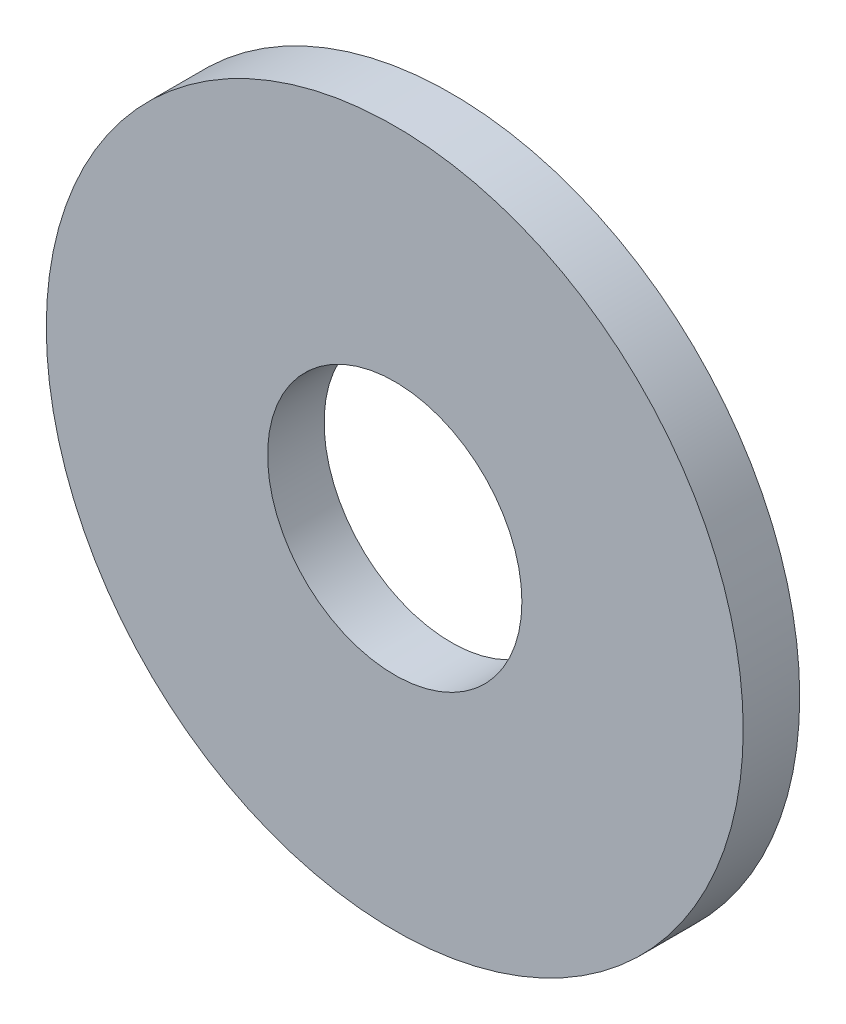
SolidWorks part; units mm, degrees
material "Nylon 101"
ref_plane "Front Plane" through (0, 0, 0) normal (0, 0, 1) x (1, 0, 0)
ref_plane "Top Plane" through (0, 0, 0) normal (0, 1, 0) x (1, 0, 0)
ref_plane "Right Plane" through (0, 0, 0) normal (1, 0, 0) x (0, 0, -1)
sketch "Sketch1" plane through (0, 0, 0) normal (0, 0, 1) x (1, 0, 0)
  circle A0 centre (0, 0) radius 7.4 construction
  circle A1 centre (0, 0) radius 2.7 construction
  point P5 (-2.7, 0)
  point P6 (2.7, 0)
  point P7 (7.4, 0)
  point P8 (-7.4, 0)
  point P9 (0, -2.7)
  dimension "OD" = 14.8
  dimension "ID" = 5.4
sketch "Sketch2" plane through (0, 0, 0) normal (1, 0, 0) x (0, 0, -1)
  line L0 (0.6, 0) -> (-0.6, 0) construction
  line L1 (0, 7.4) -> (0, -7.4) construction
  line L2 (0, 7.4) -> (0, -7.4) construction
  line L3 (0.6, 7.4) -> (-0.6, 7.4) construction
  line L4 (0.6, -7.4) -> (-0.6, -7.4) construction
  line L5 (-0.6, -7.4) -> (-0.6, 7.4) construction
  line L6 (0.6, -7.4) -> (0.6, 7.4) construction
  point P4 (0, 0)
  point P10 (0, 7.4)
  point P11 (-0.6, 7.4)
  point P14 (0, -7.4)
  point P15 (-0.6, -7.4)
  point P16 (0.6, -7.4)
  point P17 (0.6, 7.4)
  point P18 (0.6, 0)
  point P19 (-0.6, 0)
  dimension "Thickness Range" = 1.2
sketch "Sketch3" plane through (0, 0, 0) normal (0, 0, 1) x (1, 0, 0)
  circle A0 centre (0, 0) radius 7.4 construction
  circle A1 centre (0, 0) radius 2.7 construction
  circle A2 centre (0, 0) radius 7.4
  circle A3 centre (0, 0) radius 2.7
extrude "Boss-Extrude1" add sketch "Sketch3" along normal mid plane 1.2
equation "\"D1@Boss-Extrude1\"= \"Thickness Range@Sketch2\""
